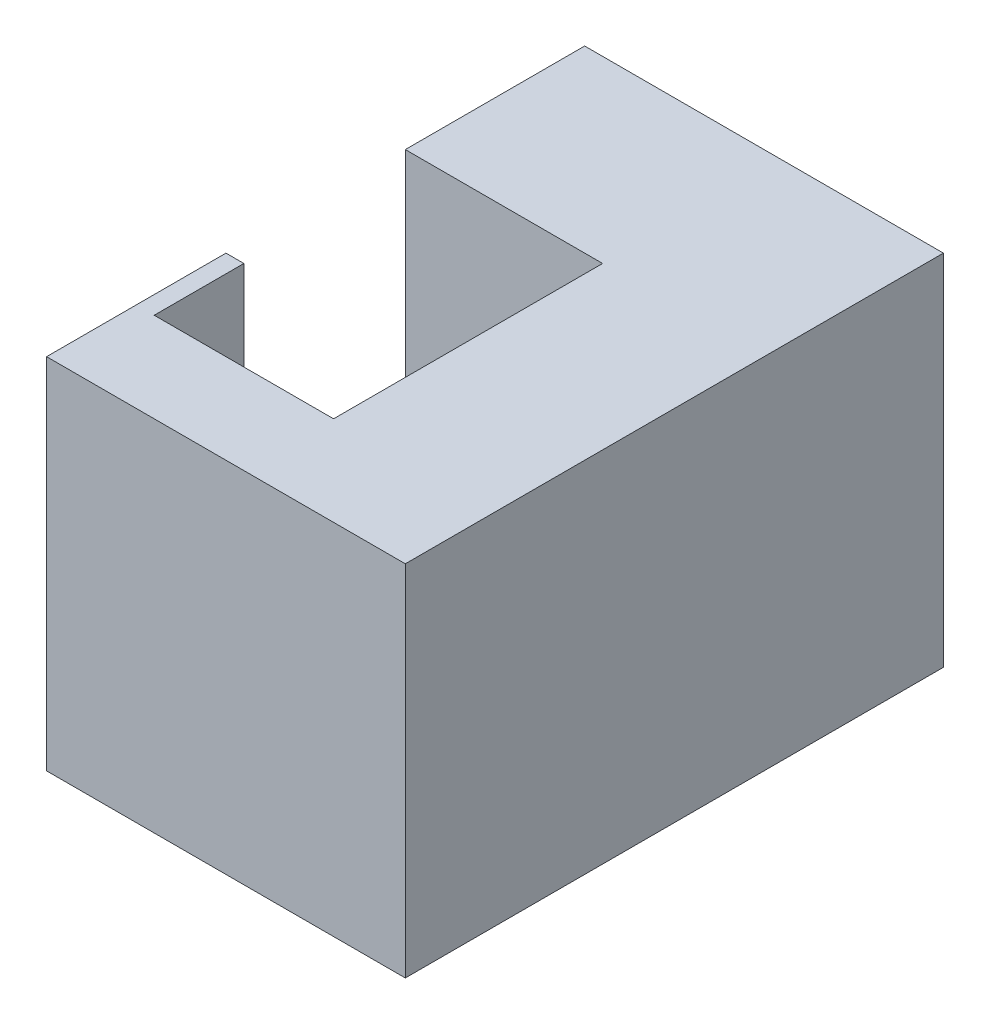
SolidWorks part; units mm, degrees
ref_plane "Front" through (0, 0, 0) normal (0, 0, 1) x (1, 0, 0)
ref_plane "Top" through (0, 0, 0) normal (0, 1, 0) x (1, 0, 0)
ref_plane "Right" through (0, 0, 0) normal (1, 0, 0) x (0, 0, -1)
sketch "Sketch2" plane through (0, 0, 0) normal (0, 1, 0) x (1, 0, 0)
  line L1 (-2.5, -3.75) -> (2.5, -3.75)
  line L2 (-2.5, -3.75) -> (-2.5, 3.75)
  line L3 (-2.5, 3.75) -> (2.5, 3.75)
  line L4 (2.5, -3.75) -> (2.5, 3.75)
  line L5 (-2.5, -3.75) -> (2.5, 3.75) construction
  line L6 (-2.5, 3.75) -> (2.5, -3.75) construction
  point P0 (0, 0)
  dimension "D1" = 5
  dimension "D2" = 7.5
extrude "Boss-Extrude1" add sketch "Sketch2" along normal blind 5
sketch "Sketch3" plane through (0, 0, 0) normal (0, -1, 0) x (1, 0, 0)
  line L0 (-2.5, -1.25) -> (0.25, -1.25)
  line L1 (-2.5, -3.75) -> (-2.5, 3.75) construction
  line L2 (0.25, -1.25) -> (0.25, 2.5)
  line L3 (0.25, 2.5) -> (-2.25, 2.5)
  line L4 (-2.25, 2.5) -> (-2.25, 1.25)
  line L5 (-2.25, 1.25) -> (-2.5, 1.25)
  line L8 (2.5, -3.75) -> (-2.5, -3.75) construction
  point P4 (0, 0)
  dimension "D1" = 2.5
  dimension "D2" = 2.75
  dimension "D3" = 3.75
  dimension "D4" = 0.25
  dimension "D5" = 2.5
extrude "Cut-Extrude1" cut sketch "Sketch3" against normal blind 5 and the other way through all
